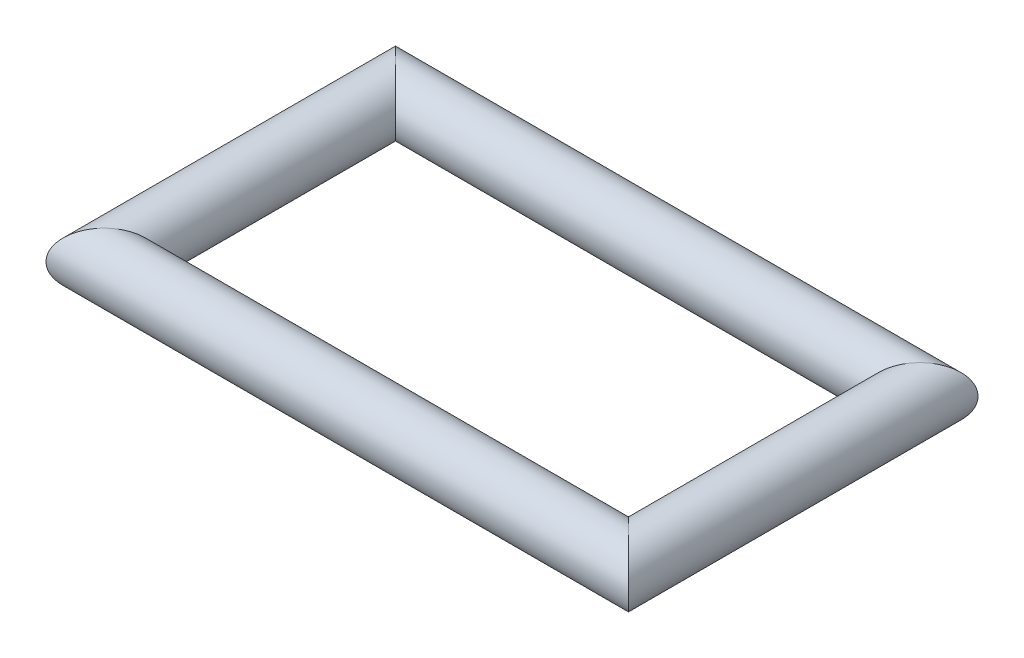
SolidWorks part; units mm, degrees
ref_plane "Alzado" through (0, 0, 0) normal (0, 0, 1) x (1, 0, 0)
ref_plane "Planta" through (0, 0, 0) normal (0, 1, 0) x (1, 0, 0)
ref_plane "Vista lateral" through (0, 0, 0) normal (1, 0, 0) x (0, 0, -1)
sketch "Croquis1" plane through (0, 0, 0) normal (0, 0, 1) x (1, 0, 0)
  line L0 (0, 186.0081) -> (0, -18.2377) construction
  line L1 (0, 6) -> (0, -6)
  line L2 (0, 6) -> (20, 6)
  line L3 (20, 6) -> (20, 21)
  line L4 (0, -6) -> (25.4512, -6)
  line L5 (25.4512, -6) -> (25.4512, 6)
  line L6 (25.4512, 6) -> (35.4512, 6)
  line L7 (35.4512, 6) -> (35.4512, 21)
  line L8 (-12.5259, 171) -> (35.4512, 171) construction
  line L9 (-12.5259, 121) -> (29.2559, 121) construction
  line L10 (25.4512, -6) -> (25.4512, 171) construction
  line L11 (15.4512, 186.0081) -> (15.4512, 93.7543) construction
  line L12 (35.4512, 21) -> (25, 21)
  line L13 (25, 21) -> (15.4512, 121)
  line L14 (10.4512, 123.1137) -> (10.4512, 118.7635) construction
  line L15 (20, 21) -> (10.4512, 121)
  line L16 (15.4512, 121) -> (15.4512, 171)
  line L17 (10.4512, 121) -> (10.4512, 163)
  line L18 (10.4512, 163) -> (0, 163)
  line L19 (15.4512, 171) -> (0, 171)
  line L20 (0, 171) -> (0, 163)
  point P5 (0, 0)
  point P23 (0, 68.7721)
  point P29 (2.7526, 186.0081)
  dimension "D1" = 12
  dimension "D2" = 20
  dimension "D3" = 15
  dimension "D4" = 177
  dimension "D5" = 50
  dimension "D6" = 10
  dimension "D7" = 10
  dimension "D8" = 5
  dimension "D9" = 8
sketch "Croquis2" plane through (0, 0, 0) normal (0, 1, 0) x (1, 0, 0)
  line L0 (15.4541, 24.4321) -> (15.4541, -25.7924) construction
  line L1 (-26.8691, 0) -> (0, 0) construction
  line L3 (0, -25) -> (90, -25)
  line L4 (0, 25) -> (90, 25)
  line L5 (0, -25) -> (0, 25)
  line L6 (90, -25) -> (90, 25)
sweep "Barrer3" add path "Croquis2" circular profile diameter 10 parameters "D3"=10
